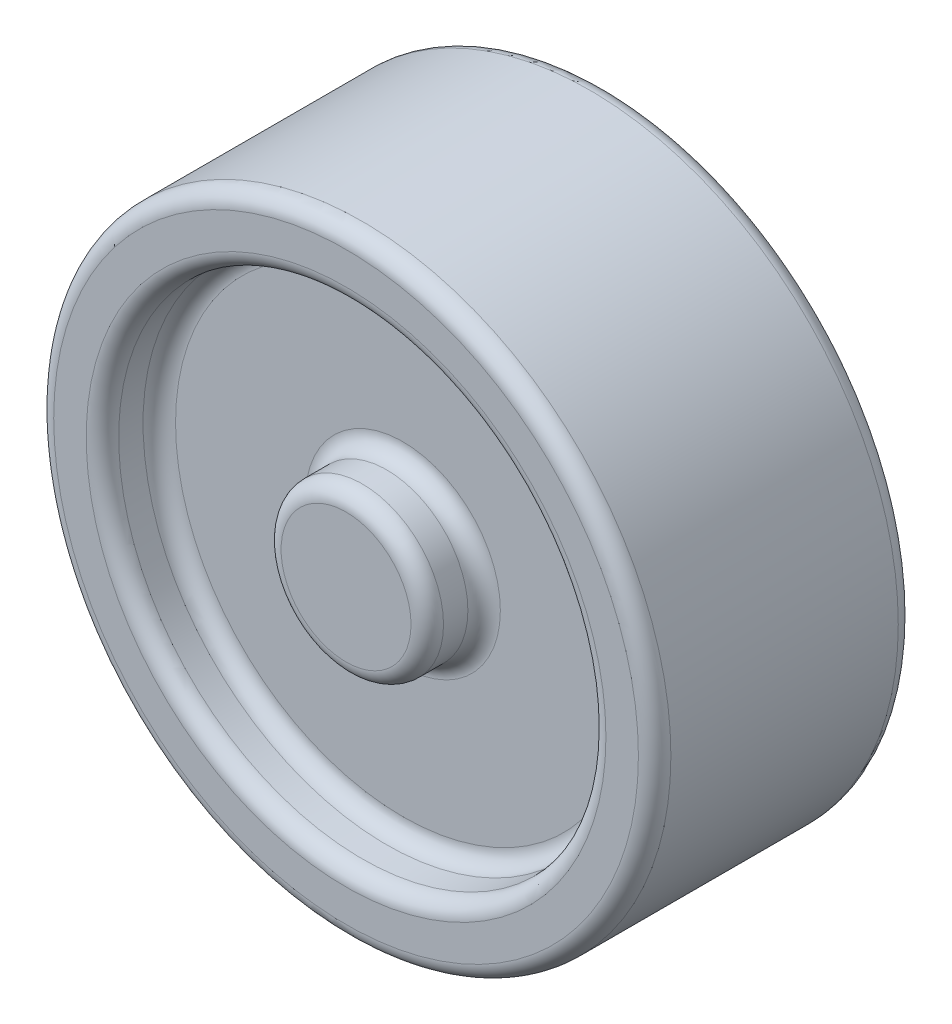
SolidWorks part; units mm, degrees
ref_plane "正面" through (0, 0, 0) normal (0, 0, 1) x (1, 0, 0)
ref_plane "平面" through (0, 0, 0) normal (0, 1, 0) x (1, 0, 0)
ref_plane "右側面" through (0, 0, 0) normal (1, 0, 0) x (0, 0, -1)
sketch "ｽｹｯﾁ1" plane through (0, 0, 0) normal (0, 0, 1) x (1, 0, 0)
  circle A0 centre (0, 0) radius 19
  dimension "D1" = 38
extrude "ﾎﾞｽ - 押し出し1" add sketch "ｽｹｯﾁ1" along normal mid plane 16
fillet "ﾌｨﾚｯﾄ1" radius 1 2 edges at (19, 0, -8) (19, 0, 8)
sketch "ｽｹｯﾁ2" plane through (0, 0, 8) normal (0, 0, 1) x (1, 0, 0)
  circle A1 centre (0, 0) radius 5
  circle A2 centre (0, 0) radius 15
  circle A3 centre (0, 0) radius 15
  dimension "D2" = 10
  dimension "D1" = 3
extrude "ｶｯﾄ - 押し出し1" cut sketch "ｽｹｯﾁ2" against normal blind 3.5
mirror "ﾐﾗｰ1" about plane through (0, 0, 0) normal (0, 0, 1) of "ｶｯﾄ - 押し出し1"
fillet "ﾌｨﾚｯﾄ2" radius 1 8 edges at (5, 0, -8) (5, 0, -4.5) (15, 0, -4.5) (15, 0, -8) (5, 0, 4.5) (5, 0, 8) (15, 0, 4.5) (15, 0, 8)
